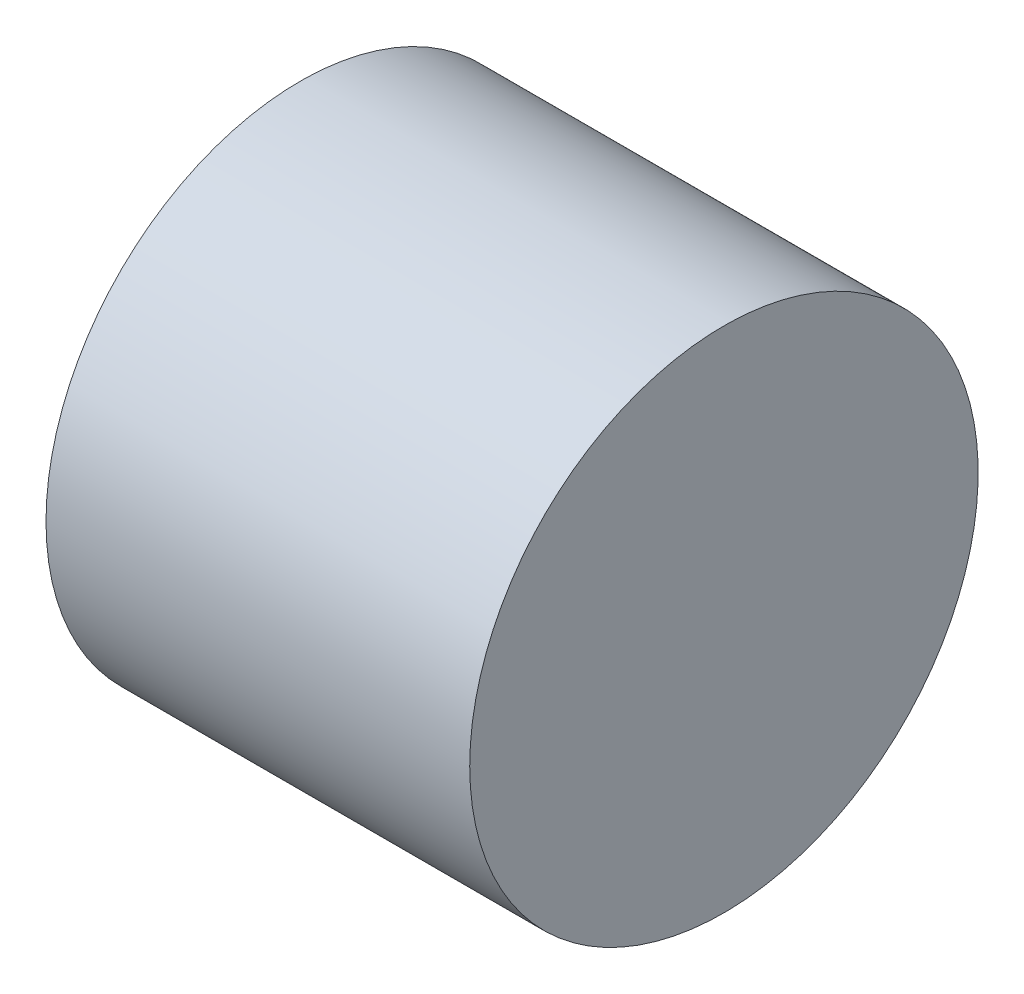
SolidWorks part; units mm, degrees
ref_plane "Front Plane" through (0, 0, 0) normal (0, 0, 1) x (1, 0, 0)
ref_plane "Top Plane" through (0, 0, 0) normal (0, 1, 0) x (1, 0, 0)
ref_plane "Right Plane" through (0, 0, 0) normal (1, 0, 0) x (0, 0, -1)
sketch "Axial blank profile" plane through (0, 0, 0) normal (0, 0, 1) x (1, 0, 0)
  line L0 (-60, 0) -> (30, 0) construction
  line L1 (-17, 0) -> (-7, 0)
  line L2 (-7, 0) -> (-7, 6)
  line L3 (-7, 6) -> (-17, 6)
  line L4 (-17, 6) -> (-17, 0)
revolve "Native revolved blank" add sketch "Axial blank profile" angle 360 about L0
